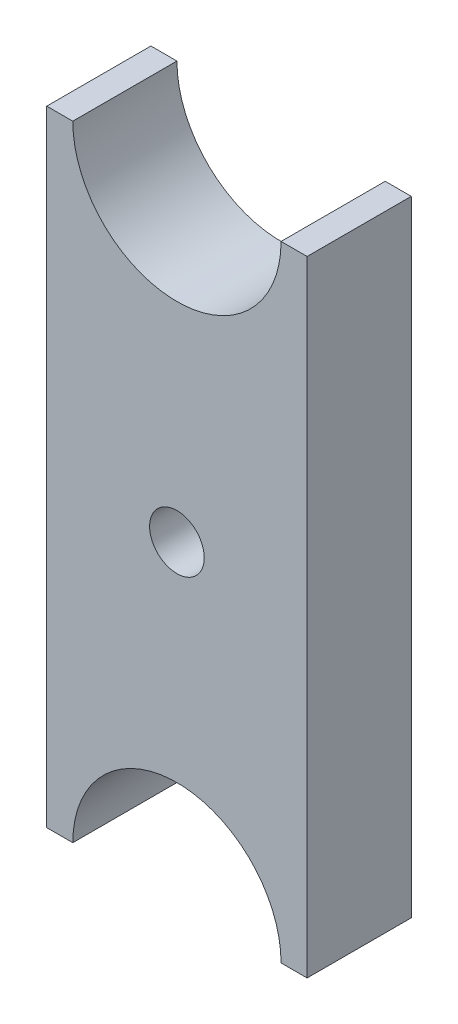
SolidWorks part; units mm, degrees
material "Ductile Iron"
ref_plane "Front Plane" through (0, 0, 0) normal (0, 0, 1) x (1, 0, 0)
ref_plane "Top Plane" through (0, 0, 0) normal (0, 1, 0) x (1, 0, 0)
ref_plane "Right Plane" through (0, 0, 0) normal (1, 0, 0) x (0, 0, -1)
sketch "Sketch1" plane through (0, 0, 0) normal (0, 0, 1) x (1, 0, 0)
  line L0 (0, 0) -> (-48956.8281, 0) construction
  line L1 (0, 0) -> (0, -48956.8281) construction
  line L2 (20, 60) -> (25, 60)
  line L3 (-25, 60) -> (-20, 60)
  line L4 (-25, 60) -> (-25, -60)
  line L5 (-25, -60) -> (-20, -60)
  line L6 (25, 60) -> (25, -60)
  line L7 (0, -60) -> (0, 60) construction
  line L8 (-25, 0) -> (25, 0) construction
  line L9 (20, -60) -> (25, -60)
  circle A0 centre (0, 0) radius 5.25
  arc A1 (20, -60) -> (-20, -60) centre (0, -60) ccw
  arc A2 (20, 60) -> (-20, 60) centre (0, 60) cw
  point P5 (0, 0)
  dimension "D1" = 120
  dimension "D2" = 10.5
  dimension "D3" = 20
  dimension "D4" = 50
  dimension "D5" = 60
extrude "Boss-Extrude1" add sketch "Sketch1" along normal blind 20
